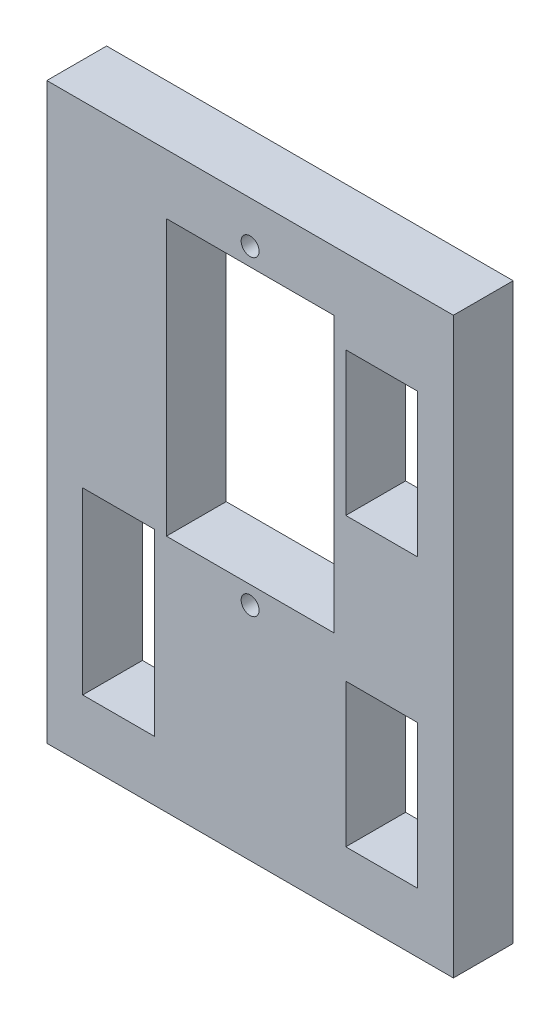
SolidWorks part; units mm, degrees
ref_plane "Alzado" through (0, 0, 0) normal (0, 0, 1) x (1, 0, 0)
ref_plane "Planta" through (0, 0, 0) normal (0, 1, 0) x (1, 0, 0)
ref_plane "Vista lateral" through (0, 0, 0) normal (1, 0, 0) x (0, 0, -1)
sketch "Croquis1" plane through (0, 0, 0) normal (0, 0, 1) x (1, 0, 0)
  line L0 (3, 48) -> (3, 0) construction
  line L1 (0, 0) -> (34, 0)
  line L2 (0, 0) -> (0, 48)
  line L3 (0, 48) -> (34, 48)
  line L4 (34, 0) -> (34, 48)
  line L5 (31, 48) -> (31, 0) construction
  line L6 (9, 48) -> (9, 0) construction
  line L7 (25, 48) -> (25, 0) construction
  line L8 (17, 48) -> (17, 0) construction
  line L10 (24, 20) -> (10, 20)
  line L11 (24, 20) -> (24, 43)
  line L12 (24, 43) -> (10, 43)
  line L13 (10, 20) -> (10, 43)
  line L14 (24, 20) -> (10, 43) construction
  line L15 (24, 43) -> (10, 20) construction
  line L16 (31, 5) -> (25, 5)
  line L17 (31, 5) -> (31, 17)
  line L18 (31, 17) -> (25, 17)
  line L19 (25, 5) -> (25, 17)
  line L20 (31, 29) -> (25, 29)
  line L21 (31, 29) -> (31, 41)
  line L22 (31, 41) -> (25, 41)
  line L23 (25, 29) -> (25, 41)
  line L24 (9, 5) -> (3, 5)
  line L25 (9, 5) -> (9, 20)
  line L26 (9, 20) -> (3, 20)
  line L27 (3, 5) -> (3, 20)
  circle A0 centre (17, 18.5) radius 0.75
  circle A1 centre (17, 44.5) radius 0.75
  point P15 (17, 31.5)
  point P36 (6, 5)
  dimension "D9" = 1.5
  dimension "D10" = 1.5
  dimension "D1" = 6
  dimension "D2" = 6
  dimension "D3" = 3
  dimension "D4" = 3
  dimension "D5" = 16
  dimension "D6" = 14
  dimension "D7" = 23
  dimension "D8" = 20
  dimension "D11" = 1.5
  dimension "D12" = 1.5
  dimension "D13" = 5
  dimension "D14" = 5
  dimension "D15" = 15
  dimension "D16" = 12
  dimension "D17" = 12
  dimension "D18" = 12
  dimension "D19" = 48
extrude "Saliente-Extruir1" add sketch "Croquis1" along normal blind 5
